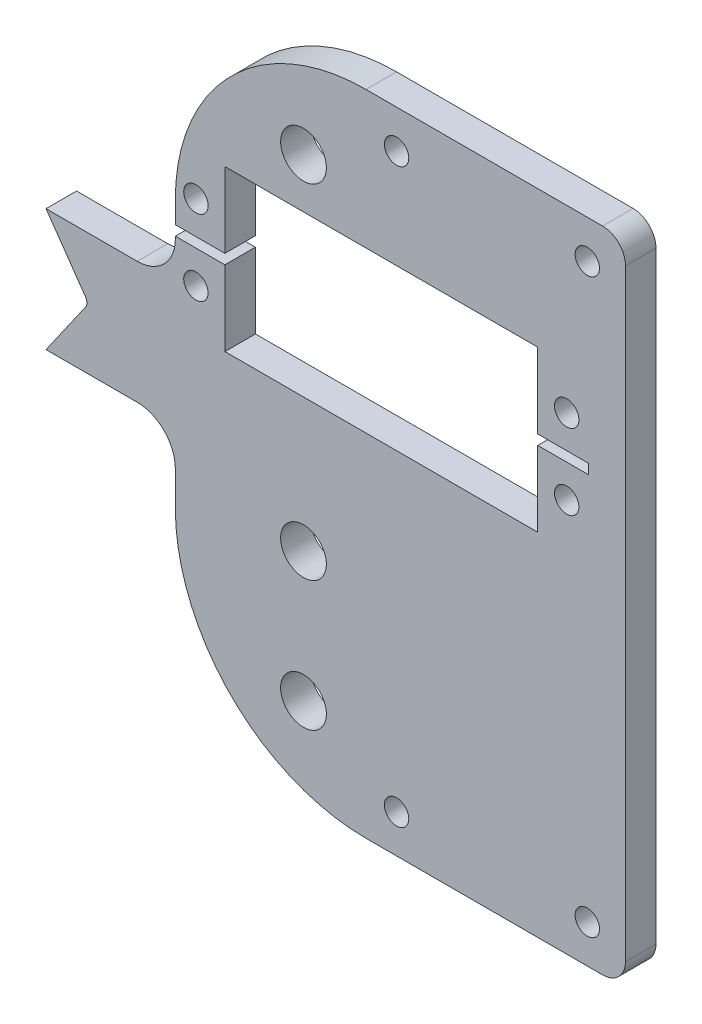
SolidWorks part; units mm, degrees
ref_plane "正面" through (0, 0, 0) normal (0, 0, 1) x (1, 0, 0)
ref_plane "平面" through (0, 0, 0) normal (0, 1, 0) x (1, 0, 0)
ref_plane "右側面" through (0, 0, 0) normal (1, 0, 0) x (0, 0, -1)
sketch "ｽｹｯﾁ1" plane through (0, 0, 0) normal (0, 0, 1) x (1, 0, 0)
  line L0 (-20, 25) -> (-20, 16.25) construction
  line L1 (-27, -31) -> (32, -31)
  line L2 (-27, -31) -> (-27, 54)
  line L3 (-27, 54) -> (32, 54)
  line L4 (32, -31) -> (32, 54)
  line L9 (-20.5, 15) -> (20.5, 15)
  line L10 (-20.5, 15) -> (-20.5, 36)
  line L11 (-20.5, 36) -> (20.5, 36)
  line L12 (20.5, 15) -> (20.5, 36)
  line L13 (-19.5, 15.5) -> (19.5, 15.5) construction
  line L14 (20, 16.25) -> (20, 25) construction
  line L15 (19.5, 35.5) -> (-19.5, 35.5) construction
  line L16 (32, 11.5) -> (-27, 11.5) construction
  line L21 (27, 17.75) -> (27, 19.05) construction
  line L24 (-27, 19.05) -> (-27, 17.75) construction
  dimension "D1" = 0.5
  dimension "D2" = 0.5
  dimension "D3" = 0.5
  dimension "D4" = 0.5
  dimension "D5" = 0
  dimension "D6" = 7
  dimension "D10" = 5
  dimension "D11" = 85
extrude "ﾎﾞｽ - 押し出し1" add sketch "ｽｹｯﾁ1" along normal blind 4
sketch "ｽｹｯﾁ2" plane through (0, 0, 0) normal (0, 0, -1) x (-1, 0, 0)
  line L5 (-20.5, 15) -> (-20.5, 36) construction
  line L6 (-20.5, 26.15) -> (-27.15, 26.15)
  line L7 (-20.5, 26.15) -> (-20.5, 24.85)
  line L8 (-20.5, 24.85) -> (-27.15, 24.85)
  line L9 (-27.15, 26.15) -> (-27.15, 24.85)
  line L10 (20.5, 36) -> (20.5, 15) construction
  line L11 (20.5, 24.85) -> (27.15, 24.85)
  line L12 (20.5, 24.85) -> (20.5, 26.15)
  line L13 (20.5, 26.15) -> (27.15, 26.15)
  line L14 (27.15, 24.85) -> (27.15, 26.15)
  line L23 (-27, 26) -> (-27, 25) construction
  line L24 (-27, 25) -> (-20, 25) construction
  line L25 (-27, 26) -> (-20, 26) construction
  line L29 (27, 25) -> (27, 26) construction
  line L30 (27, 26) -> (20, 26) construction
  line L31 (27, 25) -> (20, 25) construction
  circle A2 centre (-24.3, 20.55) radius 1.6
  circle A3 centre (-24.3, 30.45) radius 1.6
  circle A4 centre (24.3, 30.45) radius 1.6
  circle A5 centre (24.3, 20.55) radius 1.6
  dimension "D2" = 3.2
  dimension "D4" = 0.15
  dimension "D5" = 0.15
  dimension "D6" = 0.15
  dimension "D10" = 0.15
  dimension "D11" = 0.15
  dimension "D12" = 0.15
extrude "ｶｯﾄ - 押し出し1" cut sketch "ｽｹｯﾁ2" against normal blind 4
sketch "ｽｹｯﾁ5" plane through (0, 0, 4) normal (0, 0, 1) x (1, 0, 0)
  line L0 (32, 11.5) -> (-27, 11.5) construction
  line L1 (32, -31) -> (32, 54) construction
  line L2 (-27, 24.85) -> (-27, -31) construction
  line L3 (-10.2, -2.5) -> (-10.2, 25.5) construction
  circle A0 centre (-10.2, -2.5) radius 3
  circle A1 centre (-10.2, 25.5) radius 1.25 construction
  point P10 (-10.2, 11.5)
  dimension "D1" = 6
  dimension "D3" = 0
extrude "ｶｯﾄ - 押し出し4" cut sketch "ｽｹｯﾁ5" against normal blind 10
sketch "ｽｹｯﾁ3" plane through (0, 0, 4) normal (0, 0, 1) x (1, 0, 0)
  circle A0 centre (-10.2, 42.5) radius 3
  circle A1 centre (-10.2, -19.5) radius 3
  circle A10 centre (-10.2, -2.5) radius 3 construction
  circle A11 centre (-10.2, -2.5) radius 3 construction
  circle A12 centre (-10.2, 25.5) radius 1.25 construction
  circle A13 centre (-10.2, 25.5) radius 1.25 construction
  dimension "D1" = 6
  dimension "D2" = 6
  dimension "D3" = 17
  dimension "D4" = 17
  dimension "D5" = 0
  dimension "D6" = 0
extrude "ｶｯﾄ - 押し出し2" cut sketch "ｽｹｯﾁ3" against normal blind 4
fillet "ﾌｨﾚｯﾄ1" radius 25 2 edges at (-27, -31, 2) (-27, 54, 2)
fillet "ﾌｨﾚｯﾄ2" radius 3 2 edges at (32, -31, 2) (32, 54, 2)
sketch "ｽｹｯﾁ4" plane through (0, 0, 4) normal (0, 0, 1) x (1, 0, 0)
  line L0 (27, -26) -> (27, 49) construction
  line L1 (32, -28) -> (32, 51) construction
  line L2 (-2, -31) -> (29, -31) construction
  line L3 (29, 54) -> (-2, 54) construction
  circle A0 centre (27, 49) radius 1.6
  circle A1 centre (27, -26) radius 1.6
  dimension "D2" = 5
  dimension "D3" = 5
  dimension "D4" = 3.2
  dimension "D1" = 5
extrude "ｶｯﾄ - 押し出し3" cut sketch "ｽｹｯﾁ4" against normal blind 10
sketch "ｽｹｯﾁ6" plane through (0, 0, 4) normal (0, 0, 1) x (1, 0, 0)
  line L0 (-27, 19.5) -> (-43.9453, 19.5)
  line L1 (-27, 24.85) -> (-27, -6) construction
  line L2 (-43.9453, 19.5) -> (-38.3642, 11.5)
  line L3 (-38.3642, 11.5) -> (-43.9453, 3.5)
  line L4 (-43.9453, 3.5) -> (-27, 3.5)
  line L5 (-38.3642, 19.5) -> (-38.3642, 3.5) construction
  line L6 (-32, 19.5) -> (-43.9453, 19.5) construction
  line L7 (-44.0236, 3.5) -> (-32, 3.5) construction
  line L9 (-43.9453, 19.5) -> (-38.7661, 12.0762) construction
  line L10 (-27, 19.5) -> (-27, 3.5)
  dimension "D1" = 0
  dimension "D2" = 0
  dimension "D3" = 0
  dimension "D4" = 0
extrude "ﾎﾞｽ - 押し出し2" add sketch "ｽｹｯﾁ6" against normal blind 4
fillet "ﾌｨﾚｯﾄ3" radius 1 1 edges at (-38.3642, 11.5, 2)
fillet "ﾌｨﾚｯﾄ4" radius 5 2 edges at (-27, 19.5, 2) (-27, 3.5, 2)
sketch "ｽｹｯﾁ8" plane through (0, 0, 4) normal (0, 0, 1) x (1, 0, 0)
  line L1 (27, 49) -> (2, 49) construction
  line L2 (27, 49) -> (27, -26) construction
  line L3 (27, -26) -> (2, -26) construction
  line L4 (2, 49) -> (2, -26) construction
  circle A0 centre (2, -26) radius 1.6
  circle A1 centre (2, 49) radius 1.6
  circle A2 centre (27, 49) radius 1.6 construction
  point P5 (27, -26)
  point P10 (4.212, 49.3621)
  dimension "D1" = 25
extrude "ｶｯﾄ - 押し出し5" cut sketch "ｽｹｯﾁ8" against normal blind 10
